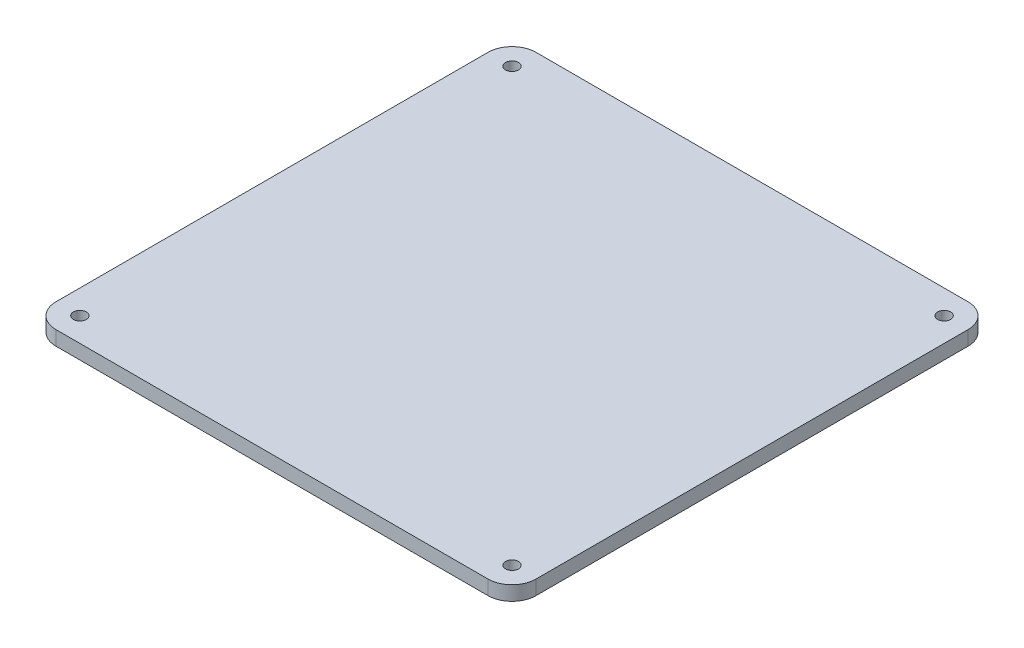
SolidWorks part; units mm, degrees
ref_plane "Front Plane" through (0, 0, 0) normal (0, 0, 1) x (1, 0, 0)
ref_plane "Top Plane" through (0, 0, 0) normal (0, 1, 0) x (1, 0, 0)
ref_plane "Right Plane" through (0, 0, 0) normal (1, 0, 0) x (0, 0, -1)
sketch "Sketch1" plane through (0, 0, 0) normal (0, 1, 0) x (1, 0, 0)
  line L1 (-100, -100) -> (100, -100)
  line L2 (-100, -100) -> (-100, 100)
  line L3 (-100, 100) -> (100, 100)
  line L4 (100, -100) -> (100, 100)
  line L5 (-100, -100) -> (100, 100) construction
  line L6 (-100, 100) -> (100, -100) construction
  point P0 (0, 0)
  dimension "D1" = 200
  dimension "D2" = 200
extrude "Boss-Extrude1" add sketch "Sketch1" along normal blind 6
fillet "Fillet1" radius 10 4 edges at (-100, 3, 100) (-100, 3, -100) (100, 3, -100) (100, 3, 100)
sketch "Sketch2" plane through (0, 6, 0) normal (0, 1, 0) x (1, 0, 0)
  arc A0 (-90, 100) -> (-100, 90) centre (-90, 90) ccw construction
  arc A1 (100, 90) -> (90, 100) centre (90, 90) ccw construction
  arc A2 (-100, -90) -> (-90, -100) centre (-90, -90) ccw construction
  arc A3 (90, -100) -> (100, -90) centre (90, -90) ccw construction
  point P0 (-90, 90)
  point P2 (90, 90)
  point P4 (90, -90)
  point P6 (-90, -90)
  point P9 (-89.5944, 91.7298)
  point P13 (0, 0)
hole_wizard "Tap Drill for 1/4-28 Tap1" positions "Sketch2" profile "Sketch4" hole size "1/4-28" standard "ANSI Inch" end condition through all
sketch "Sketch4" plane through (-90, 6, -90) normal (1, 0, 0) x (0, 0, 1)
  line L0 (0, 0) -> (0, 6)
  line L1 (0, 6) -> (2.7051, 6)
  line L2 (2.7051, 6) -> (2.7051, 0)
  line L5 (2.7051, 0) -> (0, 0)
  line L11 (0, -6.35) -> (0, 107.95) construction
  dimension "Thru Hole Dia." = 5.4102
  dimension "Thru Hole Depth" = 6
